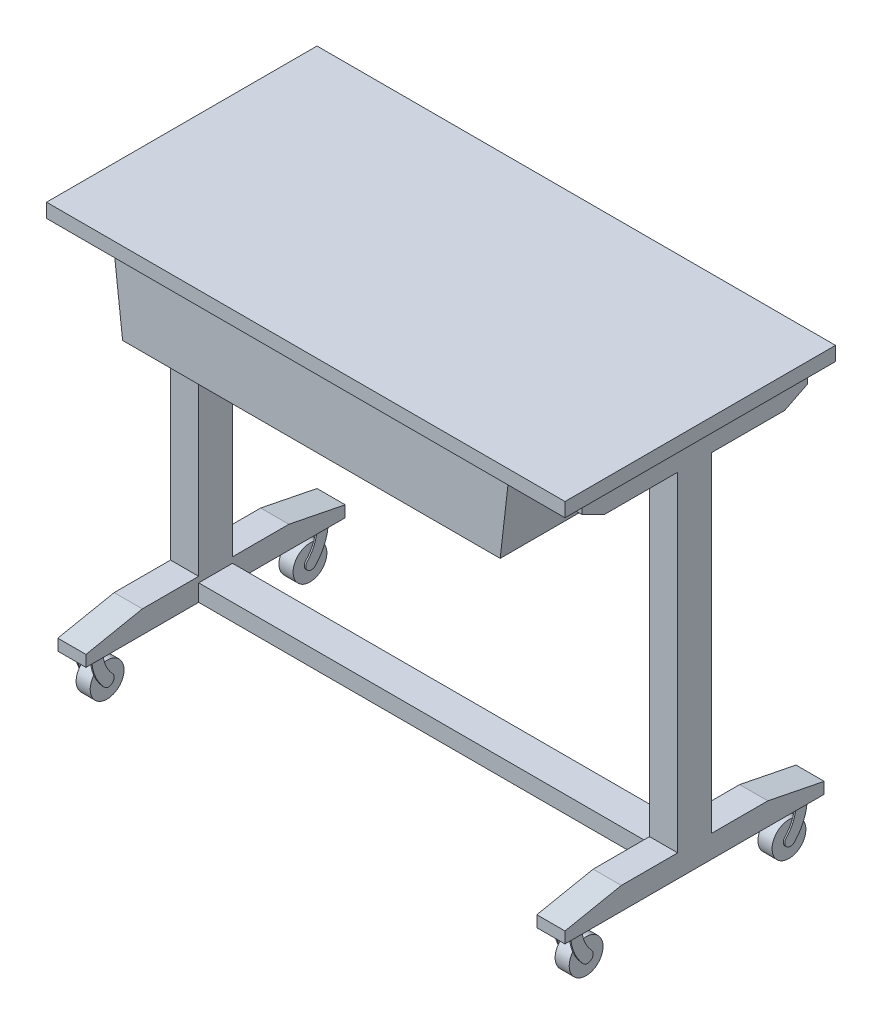
SolidWorks part; units mm, degrees
material "Plain Carbon Steel"
ref_plane "Front Plane" through (0, 0, 0) normal (0, 0, 1) x (1, 0, 0)
ref_plane "Top Plane" through (0, 0, 0) normal (0, 1, 0) x (1, 0, 0)
ref_plane "Right Plane" through (0, 0, 0) normal (1, 0, 0) x (0, 0, -1)
sketch "Sketch2" plane through (0, 0, 0) normal (0, 1, 0) x (1, 0, 0)
  line L1 (-584.2, -304.8) -> (584.2, -304.8)
  line L2 (-584.2, -304.8) -> (-584.2, 304.8)
  line L3 (-584.2, 304.8) -> (584.2, 304.8)
  line L4 (584.2, -304.8) -> (584.2, 304.8)
  line L5 (-584.2, -304.8) -> (584.2, 304.8) construction
  line L6 (-584.2, 304.8) -> (584.2, -304.8) construction
  point P0 (0, 0)
  dimension "D1" = 1168.4
  dimension "D2" = 609.6
extrude "Boss-Extrude1" add sketch "Sketch2" against normal blind 31.75
sketch "Sketch4" plane through (0, 0, 0) normal (0, 0, 1) x (1, 0, 0)
  line L0 (-584.2, -31.75) -> (584.2, -31.75) construction
  line L1 (-571.5, -31.75) -> (571.5, -31.75)
  line L2 (-571.5, -31.75) -> (-571.5, -82.55)
  line L3 (-571.5, -82.55) -> (571.5, -82.55)
  line L4 (571.5, -31.75) -> (571.5, -82.55)
  line L5 (584.2, -31.75) -> (584.2, 0) construction
  point P6 (0, -31.75)
  dimension "D1" = 12.7
  dimension "D2" = 50.8
extrude "Boss-Extrude2" add sketch "Sketch4" along normal mid plane 76.2 separate body
sketch "Sketch5" plane through (0, 0, 0) normal (0, 0, 1) x (1, 0, 0)
  line L0 (-444.5, -31.75) -> (444.5, -31.75)
  line L1 (444.5, -31.75) -> (425.45, -196.85)
  line L2 (425.45, -196.85) -> (-425.45, -196.85)
  line L3 (-425.45, -196.85) -> (-444.5, -31.75)
  line L4 (571.5, -31.75) -> (-571.5, -31.75) construction
  line L7 (-628.2169, -273.6924) -> (-77.5503, -273.6924) construction
  point P10 (0, -31.75)
  point P12 (0, -196.85)
  dimension "D2" = 165.1
  dimension "D3" = 850.9
  dimension "D4" = 889
extrude "Boss-Extrude3" add sketch "Sketch5" along normal offset from surface 12.7 and the other way offset from surface (139.7 mm away) 444.5 up to face at (0, -15.875, 304.8) other way up to face at (0, -15.875, 304.8)
ref_plane "Plane1" through (0, -977.9, 0) normal (0, 1, 0) x (1, 0, 0)
sketch "Sketch6" plane through (571.5, 0, 0) normal (1, 0, 0) x (0, 0, -1)
  line L0 (-38.1, -825.5) -> (-165.1, -825.5)
  line L2 (-38.1, -825.5) -> (-38.1, -82.55)
  line L4 (38.1, -825.5) -> (38.1, -82.55)
  line L5 (165.1, -825.5) -> (38.1, -825.5)
  line L6 (292.1, -850.9) -> (292.1, -876.3)
  line L7 (292.1, -876.3) -> (-292.1, -876.3)
  line L8 (-292.1, -850.9) -> (-292.1, -876.3)
  line L10 (304.8, -31.75) -> (304.8, 0) construction
  line L11 (335.28, -977.9) -> (-335.28, -977.9) construction
  line L13 (38.1, -82.55) -> (203.2, -82.55)
  line L14 (-254, -31.75) -> (254, -31.75)
  line L15 (-254, -31.75) -> (-254, -57.15)
  line L16 (-203.2, -82.55) -> (-38.1, -82.55)
  line L17 (254, -31.75) -> (254, -57.15)
  line L18 (-304.8, -31.75) -> (304.8, -31.75) construction
  line L19 (-38.1, -82.55) -> (38.1, -82.55) construction
  line L20 (-38.1, -82.55) -> (-38.1, -31.75) construction
  line L21 (38.1, -82.55) -> (38.1, -31.75) construction
  line L22 (-254, -57.15) -> (-203.2, -82.55)
  line L23 (203.2, -82.55) -> (254, -57.15)
  line L24 (-292.1, -850.9) -> (-165.1, -825.5)
  line L25 (165.1, -825.5) -> (292.1, -850.9)
  point P10 (0, -876.3)
  point P17 (0, -31.75)
  dimension "D1" = 12.7
  dimension "D2" = 101.6
  dimension "D3" = 50.8
  dimension "D4" = 50.8
  dimension "D5" = 50.8
  dimension "D6" = 25.4
  dimension "D7" = 25.4
  dimension "D8" = 127
extrude "Boss-Extrude4" add sketch "Sketch6" against normal blind 63.5
mirror "Mirror1" about plane through (0, 0, 0) normal (1, 0, 0) of "Boss-Extrude4"
sketch "Sketch10" plane through (0, 0, 0) normal (1, 0, 0) x (0, 0, -1)
  line L1 (-38.1, -876.3) -> (38.1, -876.3)
  line L2 (-38.1, -876.3) -> (-38.1, -838.2)
  line L3 (-38.1, -838.2) -> (38.1, -838.2)
  line L4 (38.1, -876.3) -> (38.1, -838.2)
  line L5 (-292.1, -876.3) -> (292.1, -876.3) construction
  line L6 (38.1, -825.5) -> (38.1, -82.55) construction
  line L7 (-38.1, -82.55) -> (-38.1, -825.5) construction
  dimension "D1" = 38.1
extrude "Boss-Extrude7" add sketch "Sketch10" along normal up to surface and the other way up to surface up to face at (508, -692.15, 0) other way up to face at (-508, -692.15, 0)
ref_plane "Plane2" through (539.75, 0, 0) normal (1, 0, 0) x (0, 0, -1)
sketch "Sketch8" plane through (539.75, 0, 0) normal (1, 0, 0) x (0, 0, -1)
  line L0 (335.28, -977.9) -> (-335.28, -977.9) construction
  line L1 (-292.1, -850.9) -> (-292.1, -876.3) construction
  line L2 (292.1, -876.3) -> (292.1, -850.9) construction
  circle A0 centre (-228.6, -939.8) radius 38.1
  circle A1 centre (228.6, -939.8) radius 38.1
  dimension "D1" = 76.2
  dimension "D2" = 63.5
  dimension "D3" = 63.5
extrude "Boss-Extrude5" add sketch "Sketch8" along normal mid plane 31.75 separate body
sketch "Sketch9" plane through (555.625, 0, 0) normal (1, 0, 0) x (0, 0, -1)
  line L0 (-266.7, -876.3) -> (-241.3, -876.3)
  line L1 (-292.1, -876.3) -> (292.1, -876.3) construction
  line L2 (266.7, -876.3) -> (241.3, -876.3)
  line L3 (-241.3, -876.3) -> (241.3, -876.3) construction
  arc A0 (-241.3, -876.3) -> (-219.4034, -931.0414) centre (-161.925, -876.3) ccw
  arc A1 (-219.4034, -931.0414) -> (-237.7966, -948.5586) centre (-228.6, -939.8) cw
  arc A2 (-237.7966, -948.5586) -> (-266.7, -876.3) centre (-161.925, -876.3) cw
  circle A3 centre (-228.6, -939.8) radius 38.1 construction
  arc A4 (241.3, -876.3) -> (219.4034, -931.0414) centre (161.925, -876.3) cw
  arc A5 (219.4034, -931.0414) -> (237.7966, -948.5586) centre (228.6, -939.8) ccw
  arc A6 (237.7966, -948.5586) -> (266.7, -876.3) centre (161.925, -876.3) ccw
  circle A7 centre (228.6, -939.8) radius 38.1 construction
  point P20 (210.7903, -928.5662)
  point P21 (0, -876.3)
  point P24 (254, -876.3)
  dimension "D1" = 25.4
  dimension "D2" = 25.4
extrude "Boss-Extrude6" add sketch "Sketch9" along normal blind 3.175
mirror "Mirror2" about plane through (539.75, 0, 0) normal (1, 0, 0) of "Boss-Extrude6"
mirror "Mirror3" about plane through (0, 0, 0) normal (1, 0, 0) of bodies 110 111
